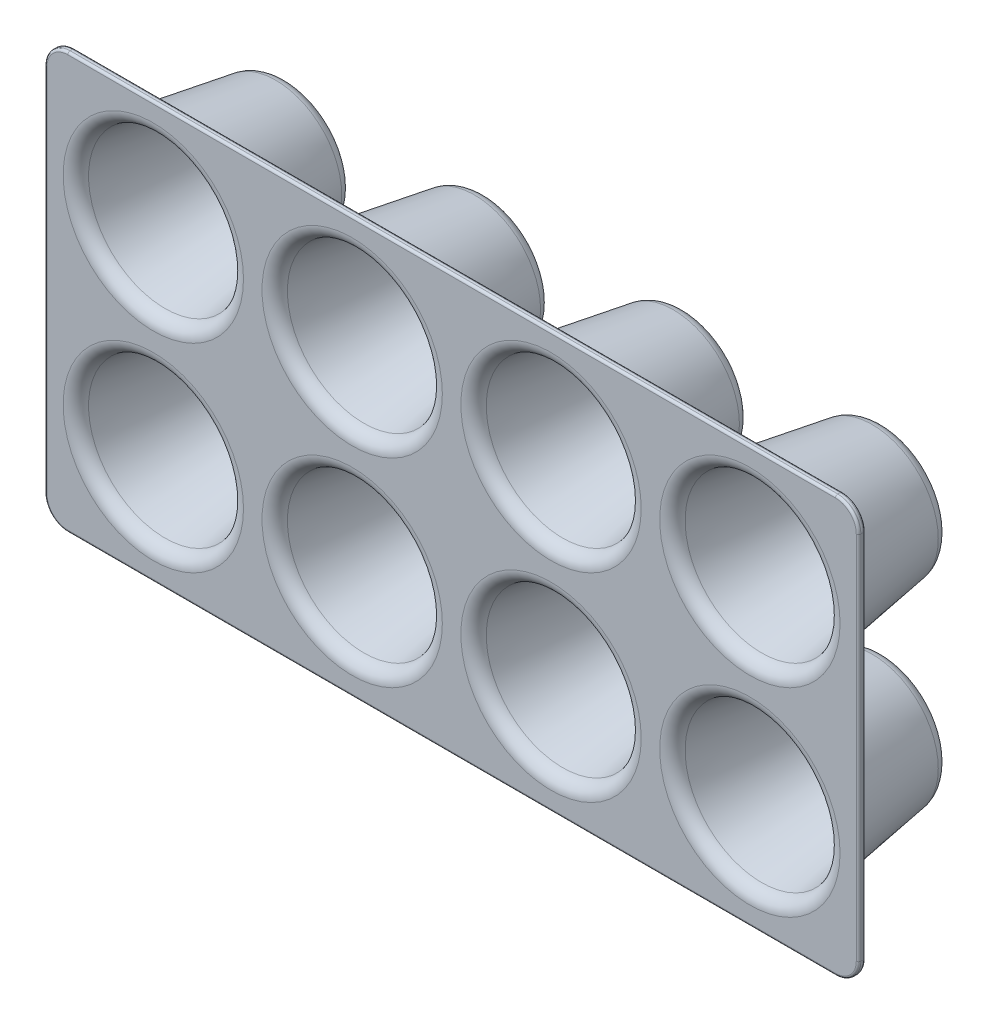
SolidWorks part; units mm, degrees
ref_plane "Front Plane" through (0, 0, 0) normal (1, 0, 0) x (0, 1, 0)
ref_plane "Top Plane" through (0, 0, 0) normal (0, 0, 1) x (0, 1, 0)
ref_plane "Right Plane" through (0, 0, 0) normal (0, 1, 0) x (-1, 0, 0)
sketch "Sketch1" plane through (0, 0, 0) normal (1, 0, 0) x (0, 1, 0)
  line L0 (-47, 0) -> (-39, 0) construction
  line L1 (-36.0369, -2.5307) -> (-28.5283, -49.9386)
  line L2 (-22.6021, -55) -> (0, -55)
  line L3 (0, 59.0602) -> (0, 21.9496) construction
  arc A0 (-39, 0) -> (-36.0369, -2.5307) centre (-39, -3) cw
  arc A1 (-28.5283, -49.9386) -> (-22.6021, -55) centre (-22.6021, -49) ccw
  point P11 (0, 0)
  point P12 (0, 0)
  dimension "D4" = 6
  dimension "D5" = 3
  dimension "D1" = 55
  dimension "D2" = 78
  dimension "D3" = 9
  dimension "D6" = 8
revolve "Revolve-Thin1" add sketch "Sketch1" angle 360 about L3 wall 3
pattern_linear "LPattern1" count 4 spacing 86 along (-1, 0, 0) count 2 spacing 86 along (0, 1, 0) of bodies 101
sketch "Sketch2" plane through (0, 0, 0) normal (0, 0, 1) x (0, 1, 0)
  line L0 (0, 172) -> (86, 86) construction
  line L1 (133, -47) -> (-47, -47)
  line L2 (133, -47) -> (133, 305)
  line L3 (133, 305) -> (-47, 305)
  line L4 (-47, -47) -> (-47, 305)
  line L5 (-47, 0) -> (0, 0) construction
  line L6 (-47, 0) -> (-39, 0) construction
  line L7 (0, 0) -> (0, -47) construction
  circle A0 centre (0, 258) radius 39 construction
  circle A1 centre (86, 258) radius 39 construction
  circle A2 centre (0, 172) radius 39 construction
  circle A3 centre (86, 172) radius 39 construction
  circle A4 centre (0, 86) radius 39 construction
  circle A5 centre (86, 86) radius 39 construction
  circle A6 centre (86, 0) radius 39 construction
  circle A7 centre (0, 0) radius 39 construction
  circle A8 centre (0, 258) radius 39
  circle A9 centre (86, 258) radius 39
  circle A10 centre (0, 172) radius 39
  circle A11 centre (86, 172) radius 39
  circle A12 centre (0, 86) radius 39
  circle A13 centre (86, 86) radius 39
  circle A14 centre (86, 0) radius 39
  circle A15 centre (0, 0) radius 39
  point P9 (43, 129)
  point P10 (43, 305)
  point P11 (-47, 129)
extrude "Boss-Extrude1" add sketch "Sketch2" along normal blind 3
fillet "Fillet1" radius 10 4 edges at (47, 133, 1.5) (47, -47, 1.5) (-305, 133, 1.5) (-305, -47, 1.5)
fillet "Fillet2" radius 1 16 edges at (47, 43, 0) (44.0711, 130.0711, 0) (-129, 133, 0) (-302.0711, 130.0711, 0) (-305, 43, 0) (-302.0711, -44.0711, 0) (-129, -47, 0) (-302.0711, -44.0711, 3) (-305, 43, 3) (-302.0711, 130.0711, 3) (-129, 133, 3) (44.0711, 130.0711, 3) (47, 43, 3) (44.0711, -44.0711, 3) (44.0711, -44.0711, 0) (-129, -47, 3)
